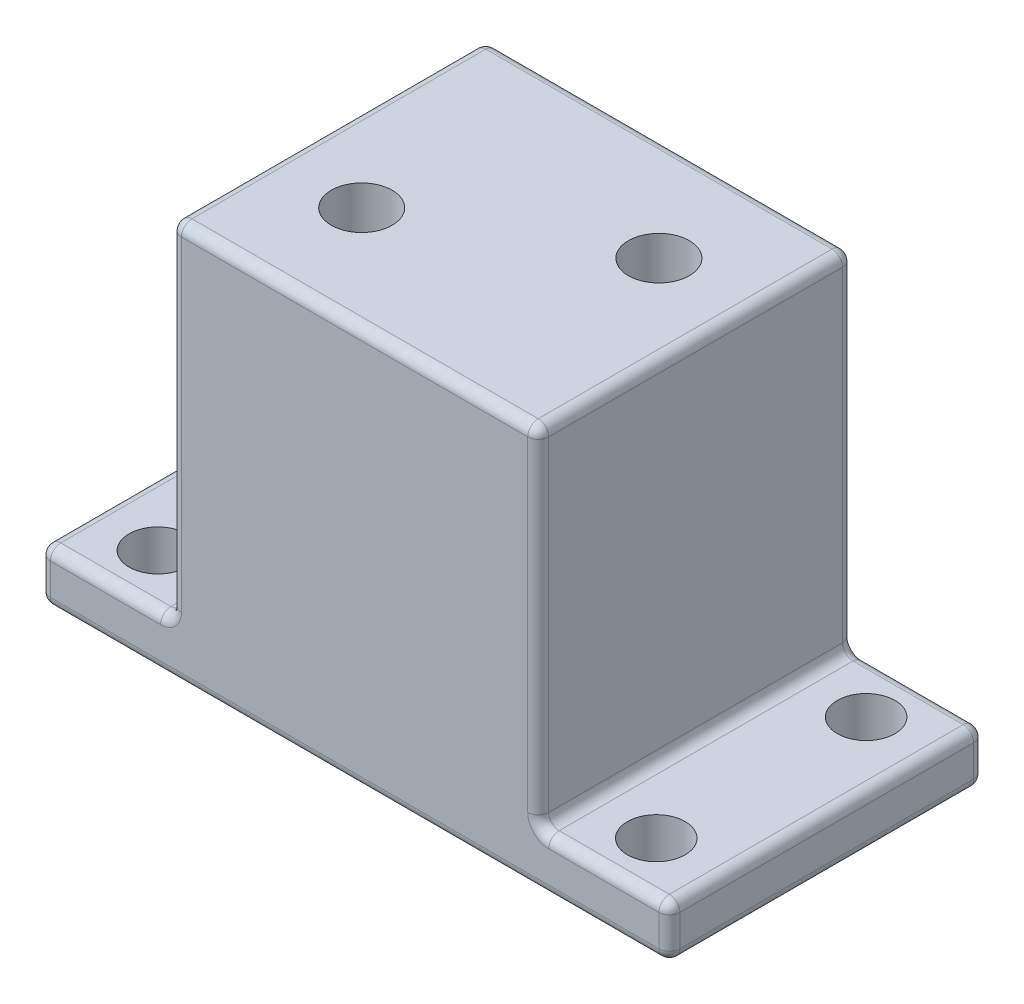
SolidWorks part; units mm, degrees
ref_plane "Front Plane" through (0, 0, 0) normal (0, 0, 1) x (1, 0, 0)
ref_plane "Top Plane" through (0, 0, 0) normal (0, 1, 0) x (1, 0, 0)
ref_plane "Right Plane" through (0, 0, 0) normal (1, 0, 0) x (0, 0, -1)
sketch "Sketch2" plane through (0, 0, 0) normal (0, 1, 0) x (1, 0, 0)
  line L1 (0, 0) -> (-60, 0)
  line L2 (0, 0) -> (0, -30)
  line L3 (0, -30) -> (-60, -30)
  line L4 (-60, 0) -> (-60, -30)
  dimension "D1" = 60
  dimension "D2" = 30
extrude "Boss-Extrude1" add sketch "Sketch2" along normal blind 5
sketch "Sketch3" plane through (0, 5, 0) normal (0, 1, 0) x (1, 0, 0)
  line L0 (0, -30) -> (-60, 0) construction
  line L1 (0, 0) -> (-60, 0) construction
  line L2 (-47.5, -30) -> (-12.5, -30)
  line L3 (-47.5, -30) -> (-47.5, 0)
  line L4 (-47.5, 0) -> (-12.5, 0)
  line L5 (-12.5, -30) -> (-12.5, 0)
  line L6 (-47.5, -30) -> (-12.5, 0) construction
  line L7 (-47.5, 0) -> (-12.5, -30) construction
  point P4 (-30, -15)
  dimension "D1" = 35
extrude "Boss-Extrude2" add sketch "Sketch3" along normal blind 33
sketch "Sketch5" plane through (0, 38, 0) normal (0, 1, 0) x (1, 0, 0)
  line L0 (-39.325, 0) -> (-39.325, -20) construction
  line L1 (-12.5, 0) -> (-47.5, 0) construction
  line L2 (-39.325, -20) -> (0, -20) construction
  line L3 (0, -30) -> (0, 0) construction
  line L4 (0, -10) -> (-21, -10) construction
  line L5 (-21, -10) -> (-21, 0) construction
  circle A0 centre (-21, -10) radius 2.9
  circle A1 centre (-39.325, -20) radius 2.9
  dimension "D5" = 5.8
  dimension "D1" = 21
  dimension "D2" = 10
  dimension "D3" = 20
  dimension "D4" = 39.325
extrude "Cut-Extrude1" cut sketch "Sketch5" against normal blind 20
sketch "Sketch6" plane through (0, 5, 0) normal (0, 1, 0) x (1, 0, 0)
  line L0 (-53.75, 0) -> (-53.75, -5) construction
  line L3 (-47.5, 0) -> (-60, 0) construction
  line L6 (-53.75, -5) -> (-53.75, -25) construction
  line L7 (-53.75, -25) -> (-53.75, -30) construction
  line L8 (-60, -30) -> (-47.5, -30) construction
  line L9 (-6.25, -30) -> (-6.25, -25) construction
  line L10 (-12.5, -30) -> (0, -30) construction
  line L11 (-6.25, -25) -> (-6.25, -5) construction
  line L12 (-6.25, -5) -> (-6.25, 0) construction
  line L13 (0, 0) -> (-12.5, 0) construction
  circle A0 centre (-6.25, -5) radius 2.75
  circle A1 centre (-6.25, -25) radius 2.75
  circle A2 centre (-53.75, -25) radius 2.75
  circle A3 centre (-53.75, -5) radius 2.75
  dimension "D2" = 5.5
  dimension "D1" = 5
extrude "Cut-Extrude2" cut sketch "Sketch6" against normal through all
fillet "Fillet1" radius 1 24 edges at (-12.5, 38, 15) (-12.5, 5, 15) (-47.5, 38, 15) (-47.5, 5, 15) (-60, 5, 15) (-60, 0, 15) (0, 5, 15) (0, 0, 15) (0, 2.5, 0) (-6.25, 5, 0) (-12.5, 21.5, 0) (-30, 38, 0) (-47.5, 21.5, 0) (-53.75, 5, 0) (-60, 2.5, 0) (-30, 0, 0) (-60, 2.5, 30) (-53.75, 5, 30) (-47.5, 21.5, 30) (-30, 38, 30) (-12.5, 21.5, 30) (-6.25, 5, 30) (0, 2.5, 30) (-30, 0, 30)
